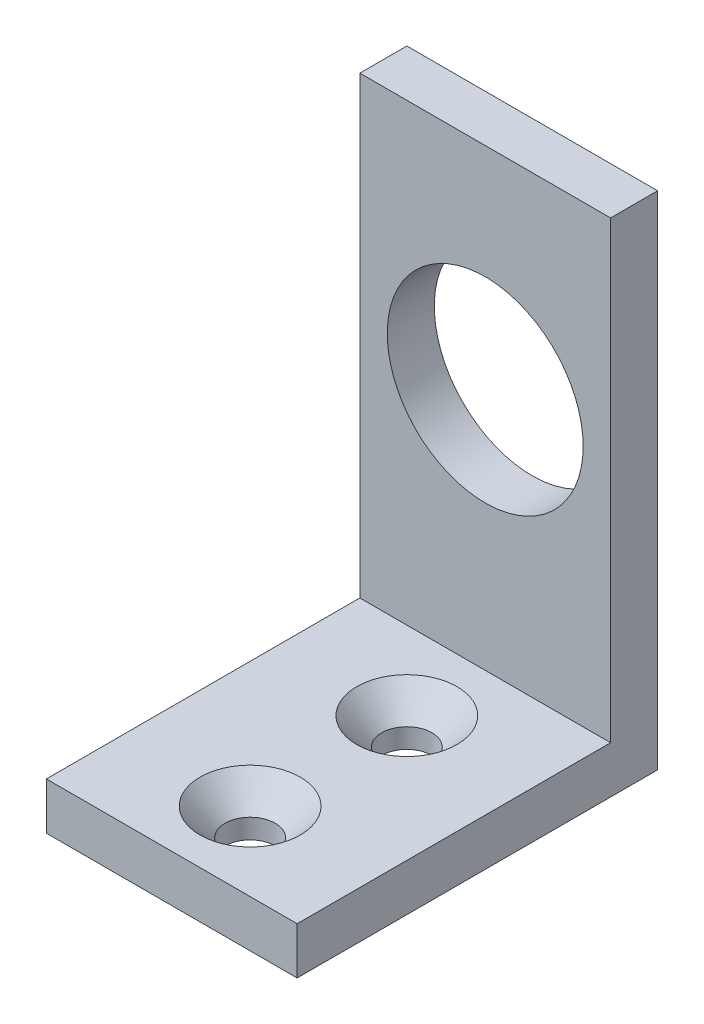
SolidWorks part; units mm, degrees
ref_plane "Front Plane" through (0, 0, 0) normal (0, 0, 1) x (1, 0, 0)
ref_plane "Top Plane" through (0, 0, 0) normal (0, 1, 0) x (1, 0, 0)
ref_plane "Right Plane" through (0, 0, 0) normal (1, 0, 0) x (0, 0, -1)
sketch "Sketch1" plane through (0, 0, 0) normal (1, 0, 0) x (0, 0, -1)
  line L0 (23, 0) -> (23, 29)
  line L1 (0, 0) -> (23, 0)
  line L2 (0, 0) -> (0, -3)
  line L3 (0, -3) -> (23, -3)
  line L4 (23, 0) -> (23, -3)
  line L5 (23, 29) -> (20, 29)
  line L6 (20, 29) -> (20, 0)
  dimension "D1" = 20
  dimension "D2" = 29
  dimension "D3" = 3
  dimension "D4" = 3
extrude "Boss-Extrude1" add sketch "Sketch1" along normal blind 16 contours L4 L1 L2 L3 | L5 L6 L1 L0
sketch "Sketch2" plane through (0, 0, 0) normal (0, 1, 0) x (1, 0, 0)
  line L0 (8, 0) -> (8, 20) construction
  line L1 (16, 0) -> (0, 0) construction
  line L2 (16, 20) -> (0, 20) construction
  point P0 (8, 5)
  point P1 (8, 15)
  point P10 (8, 10)
  dimension "D1" = 5
  dimension "D2" = 5
hole_wizard "Hole1" positions "3DSketch1" profile "Sketch4" legacy end condition through all
sketch3d "3DSketch1"
  point P0 (8, 0, -5)
  point P3 (8, 0, -15)
sketch "Sketch4" plane through (8, 0, -5) normal (1, 0, 0) x (0, 0, 1)
  line L0 (0, 0) -> (0, 3)
  line L1 (0, 3) -> (1.6, 3)
  line L2 (1.6, 3) -> (1.6, 1.7461)
  line L3 (1.6, 1.7461) -> (3.2, 0)
  line L4 (3.2, 0) -> (0, 0)
  line L5 (0, -6.4453) -> (0, 115.525) construction
  line L6 (-1.6, 1.7461) -> (-3.2, 0) construction
  dimension "Diameter" = 3.2
  dimension "Depth" = 3
  dimension "C-Sink Angle" = 85
  dimension "C-Sink Diameter" = 6.4
sketch "Sketch5" plane through (0, 0, -20) normal (0, 0, 1) x (1, 0, 0)
  line L0 (0, 14.5) -> (16, 14.5) construction
  line L1 (0, 29) -> (0, 0) construction
  line L2 (16, 29) -> (16, 0) construction
  line L4 (8, 14.5) -> (8, 15.5) construction
  circle A0 centre (8, 15.5) radius 6.25
  dimension "D1" = 12.5
  dimension "D2" = 1
extrude "Cut-Extrude1" cut sketch "Sketch5" against normal through all
